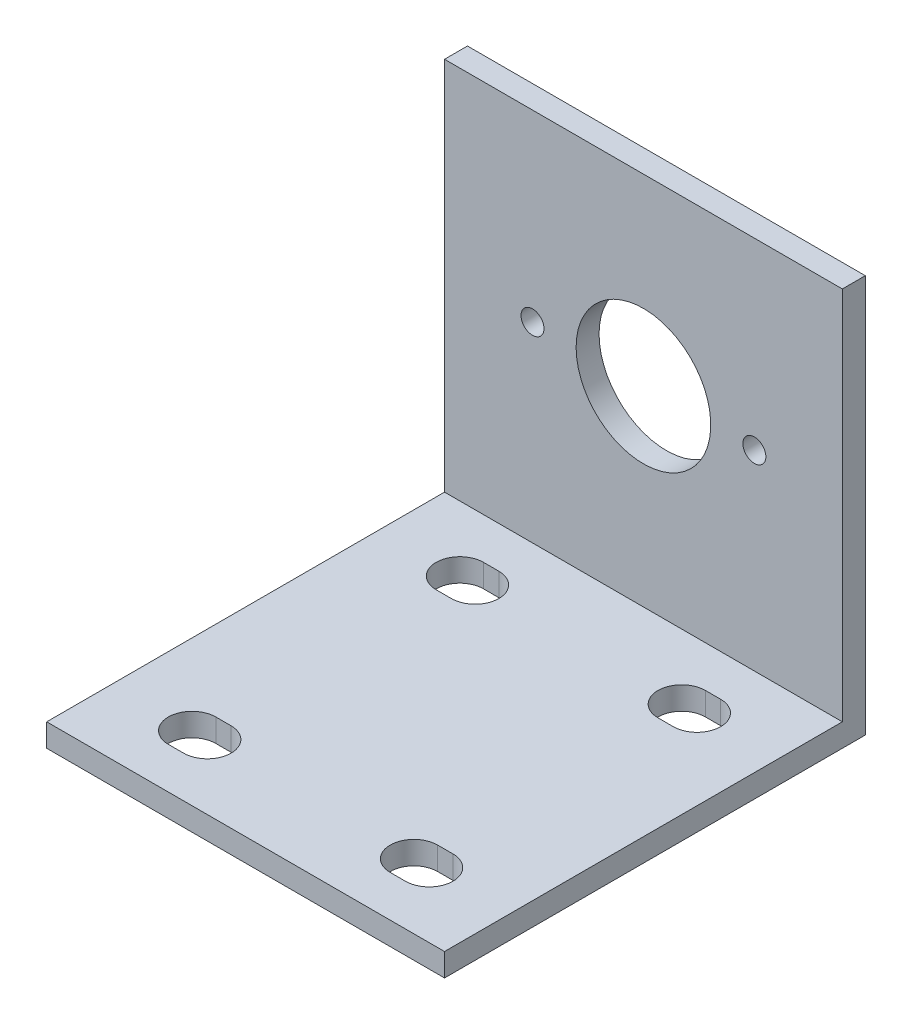
SolidWorks part; units mm, degrees
ref_plane "前基準面" through (0, 0, 0) normal (0, 0, 1) x (1, 0, 0)
ref_plane "上基準面" through (0, 0, 0) normal (0, 1, 0) x (1, 0, 0)
ref_plane "右基準面" through (0, 0, 0) normal (1, 0, 0) x (0, 0, -1)
sketch "草圖1" plane through (0, 0, 0) normal (0, 1, 0) x (1, 0, 0)
  line L0 (-15.5, 17.5) -> (-13.5, 17.5) construction
  line L1 (26, 26) -> (-26, 26)
  line L2 (26, 26) -> (26, -26)
  line L3 (26, -26) -> (-26, -26)
  line L4 (-26, 26) -> (-26, -26)
  line L5 (0, -26) -> (0, 26) construction
  line L6 (26, 0) -> (-26, 0) construction
  line L7 (-15.5, 20.6) -> (-13.5, 20.6)
  line L8 (-15.5, 14.4) -> (-13.5, 14.4)
  line L9 (15.5, 17.5) -> (13.5, 17.5) construction
  line L10 (15.5, 20.6) -> (13.5, 20.6)
  line L11 (15.5, 14.4) -> (13.5, 14.4)
  line L12 (15.5, -17.5) -> (13.5, -17.5) construction
  line L13 (15.5, -20.6) -> (13.5, -20.6)
  line L14 (15.5, -14.4) -> (13.5, -14.4)
  line L15 (-15.5, -17.5) -> (-13.5, -17.5) construction
  line L16 (-15.5, -20.6) -> (-13.5, -20.6)
  line L17 (-15.5, -14.4) -> (-13.5, -14.4)
  arc A0 (-15.5, 20.6) -> (-15.5, 14.4) centre (-15.5, 17.5) ccw
  arc A1 (-13.5, 14.4) -> (-13.5, 20.6) centre (-13.5, 17.5) ccw
  arc A2 (15.5, 20.6) -> (15.5, 14.4) centre (15.5, 17.5) cw
  arc A3 (13.5, 14.4) -> (13.5, 20.6) centre (13.5, 17.5) cw
  arc A4 (15.5, -20.6) -> (15.5, -14.4) centre (15.5, -17.5) ccw
  arc A5 (13.5, -14.4) -> (13.5, -20.6) centre (13.5, -17.5) ccw
  arc A6 (-15.5, -20.6) -> (-15.5, -14.4) centre (-15.5, -17.5) cw
  arc A7 (-13.5, -14.4) -> (-13.5, -20.6) centre (-13.5, -17.5) cw
  point P0 (0, 0)
  point P6 (-14.5, 17.5)
  point P19 (14.5, 17.5)
  point P26 (14.5, -17.5)
  point P33 (-14.5, -17.5)
  dimension "D3" = 3.1
  dimension "D1" = 52
  dimension "D2" = 52
  dimension "D4" = 2
  dimension "D5" = 35
  dimension "D6" = 29
extrude "填料-伸長1" add sketch "草圖1" along normal blind 3
sketch "草圖2" plane through (0, 0, -26) normal (0, 0, -1) x (-1, 0, 0)
  line L0 (-26, 3) -> (-26, 0) construction
  line L1 (26, 0) -> (-26, 0)
  line L2 (26, 0) -> (26, 52)
  line L3 (26, 52) -> (-26, 52)
  line L4 (-26, 0) -> (-26, 52)
  line L5 (0, 58.3104) -> (0, -5.5003) construction
  circle A0 centre (-14.5, 28) radius 1.5
  circle A1 centre (14.5, 28) radius 1.5
  circle A2 centre (0, 28) radius 8.8
  dimension "D2" = 3
  dimension "D5" = 17.6
  dimension "D1" = 52
  dimension "D3" = 29
  dimension "D4" = 24
extrude "填料-伸長2" add sketch "草圖2" along normal blind 3
